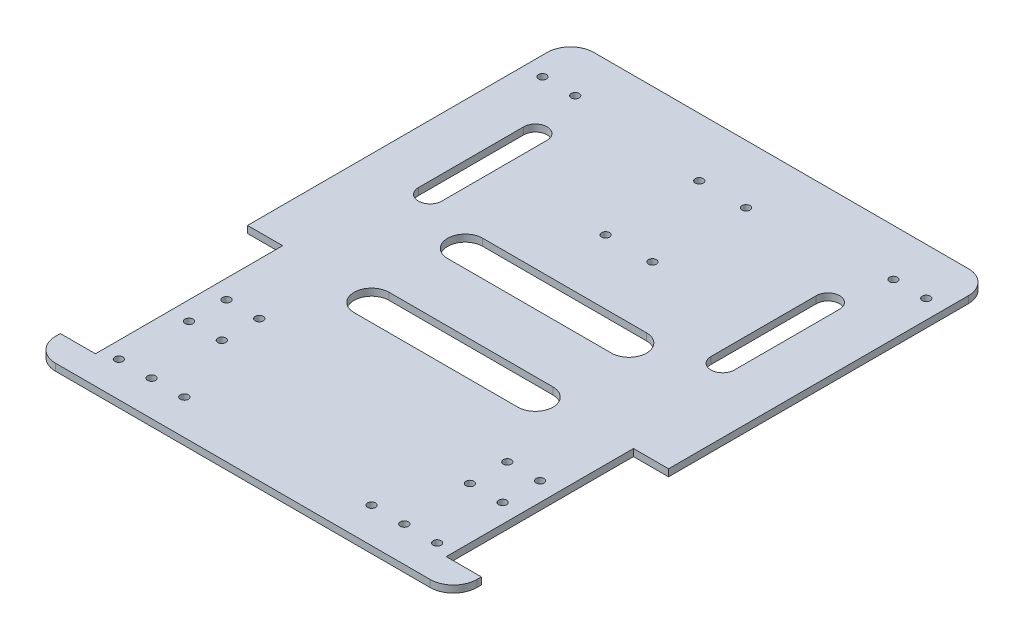
SolidWorks part; units mm, degrees
ref_plane "Front Plane" through (0, 0, 0) normal (0, 0, 1) x (1, 0, 0)
ref_plane "Top Plane" through (0, 0, 0) normal (0, 1, 0) x (1, 0, 0)
ref_plane "Right Plane" through (0, 0, 0) normal (1, 0, 0) x (0, 0, -1)
sketch "Sketch1" plane through (0, 0, 0) normal (0, 1, 0) x (1, 0, 0)
  line L1 (-90, 140) -> (90, 140)
  line L2 (-90, 140) -> (-90, -90)
  line L3 (-90, -90) -> (90, -90)
  line L4 (90, 140) -> (90, -90)
  line L5 (-90, 140) -> (90, -90) construction
  line L6 (-90, -90) -> (90, 140) construction
  point P0 (0, 25)
  dimension "D1" = 230
  dimension "D2" = 180
  dimension "D3" = 25
extrude "Boss-Extrude1" add sketch "Sketch1" along normal blind 3
fillet "Fillet1" radius 10 4 edges at (-90, 1.5, -140) (-90, 1.5, 90) (90, 1.5, -140) (90, 1.5, 90)
sketch "Sketch2" plane through (0, 3, 0) normal (0, 1, 0) x (1, 0, 0)
  circle A0 centre (-82, 120) radius 1.7
  circle A1 centre (-68, 120) radius 1.7
  circle A2 centre (68, 120) radius 1.7
  circle A3 centre (82, 120) radius 1.7
  circle A4 centre (-82, -75) radius 1.7
  circle A5 centre (-68, -75) radius 1.7
  circle A6 centre (68, -75) radius 1.7
  circle A7 centre (82, -75) radius 1.7
  circle A24 centre (-67, -30) radius 1.7
  circle A25 centre (-67, -46) radius 1.7
  circle A26 centre (-53, -30) radius 1.7
  circle A27 centre (-53, -46) radius 1.7
  circle A28 centre (53, -30) radius 1.7
  circle A29 centre (53, -46) radius 1.7
  circle A30 centre (67, -30) radius 1.7
  circle A31 centre (67, -46) radius 1.7
  circle A32 centre (-54, -75) radius 1.7
  circle A33 centre (54, -75) radius 1.7
  circle A34 centre (-40, -75) radius 1.7
  circle A35 centre (40, -75) radius 1.7
  dimension "D1" = 3.4
  dimension "D10" = 30
  dimension "D11" = 14
  dimension "D13" = 14
  dimension "D14" = 14
  dimension "D17" = 3.4
  dimension "D18" = 14
  dimension "D19" = 14
  dimension "D20" = 14
  dimension "D2" = 14
  dimension "D3" = 14
  dimension "D4" = 82
  dimension "D5" = 82
  dimension "D6" = 120
  dimension "D7" = 75
  dimension "D12" = 16
  dimension "D15" = 67
  dimension "D16" = 67
extrude "Cut-Extrude1" cut sketch "Sketch2" against normal up to surface (3 mm away) up to face at (0, 0, -25)
sketch "Sketch3" plane through (0, 3, 0) normal (0, 1, 0) x (1, 0, 0)
  circle A4 centre (10, 75) radius 1.7
  circle A5 centre (-10, 75) radius 1.7
  circle A6 centre (-10, 115) radius 1.7
  circle A7 centre (10, 115) radius 1.7
  dimension "D1" = 3.4
  dimension "D6" = 20
  dimension "D8" = 40
  dimension "D9" = 75
  dimension "D7" = 10
extrude "Cut-Extrude2" cut sketch "Sketch3" against normal up to surface (3 mm away) up to face at (-67, 0, 31.7)
sketch "Sketch7" plane through (0, 3, 0) normal (0, 1, 0) x (1, 0, 0)
  line L0 (-90, 130) -> (-90, -80) construction
  line L1 (-105, 2) -> (-75, 2)
  line L2 (-105, 2) -> (-105, -78)
  line L3 (-105, -78) -> (-75, -78)
  line L4 (-75, 2) -> (-75, -78)
  line L5 (-105, 2) -> (-75, -78) construction
  line L6 (-105, -78) -> (-75, 2) construction
  line L7 (90, -80) -> (90, 130) construction
  line L8 (75, 1.9002) -> (105, 1.9002)
  line L9 (75, 1.9002) -> (75, -78.0998)
  line L10 (75, -78.0998) -> (105, -78.0998)
  line L11 (105, 1.9002) -> (105, -78.0998)
  line L12 (75, 1.9002) -> (105, -78.0998) construction
  line L13 (75, -78.0998) -> (105, 1.9002) construction
  circle A0 centre (-67, -30) radius 1.7 construction
  point P0 (-90, -38)
  point P7 (90, -38.0998)
  dimension "D1" = 80
  dimension "D2" = 15
  dimension "D3" = 8
extrude "Cut-Extrude7" cut sketch "Sketch7" against normal through all
sketch "Sketch8" plane through (0, 3, 0) normal (0, 1, 0) x (1, 0, 0)
  line L0 (-35, 40) -> (35, 40) construction
  line L1 (-35, 47.5) -> (35, 47.5)
  line L2 (-35, 32.5) -> (35, 32.5)
  line L3 (-35, 0) -> (35, 0) construction
  line L4 (-35, 7.5) -> (35, 7.5)
  line L5 (-35, -7.5) -> (35, -7.5)
  line L6 (-62.5, 97.5) -> (-62.5, 52.5) construction
  line L7 (-57.5, 97.5) -> (-57.5, 52.5)
  line L8 (-67.5, 97.5) -> (-67.5, 52.5)
  line L9 (62.5, 97.5) -> (62.5, 52.5) construction
  line L10 (67.5, 97.5) -> (67.5, 52.5)
  line L11 (57.5, 97.5) -> (57.5, 52.5)
  arc A0 (-35, 47.5) -> (-35, 32.5) centre (-35, 40) ccw
  arc A1 (35, 32.5) -> (35, 47.5) centre (35, 40) ccw
  arc A2 (-35, 7.5) -> (-35, -7.5) centre (-35, 0) ccw
  arc A3 (35, -7.5) -> (35, 7.5) centre (35, 0) ccw
  arc A4 (-57.5, 97.5) -> (-67.5, 97.5) centre (-62.5, 97.5) ccw
  arc A5 (-67.5, 52.5) -> (-57.5, 52.5) centre (-62.5, 52.5) ccw
  arc A6 (67.5, 97.5) -> (57.5, 97.5) centre (62.5, 97.5) ccw
  arc A7 (57.5, 52.5) -> (67.5, 52.5) centre (62.5, 52.5) ccw
  point P2 (0, 40)
  point P7 (0, 0)
  point P14 (-62.5, 75)
  point P22 (62.5, 75)
  dimension "D1" = 70
  dimension "D2" = 40
  dimension "D3" = 15
  dimension "D4" = 125
  dimension "D5" = 62.5
  dimension "D6" = 45
  dimension "D7" = 10
  dimension "D8" = 75
extrude "Cut-Extrude8" cut sketch "Sketch8" against normal through all
